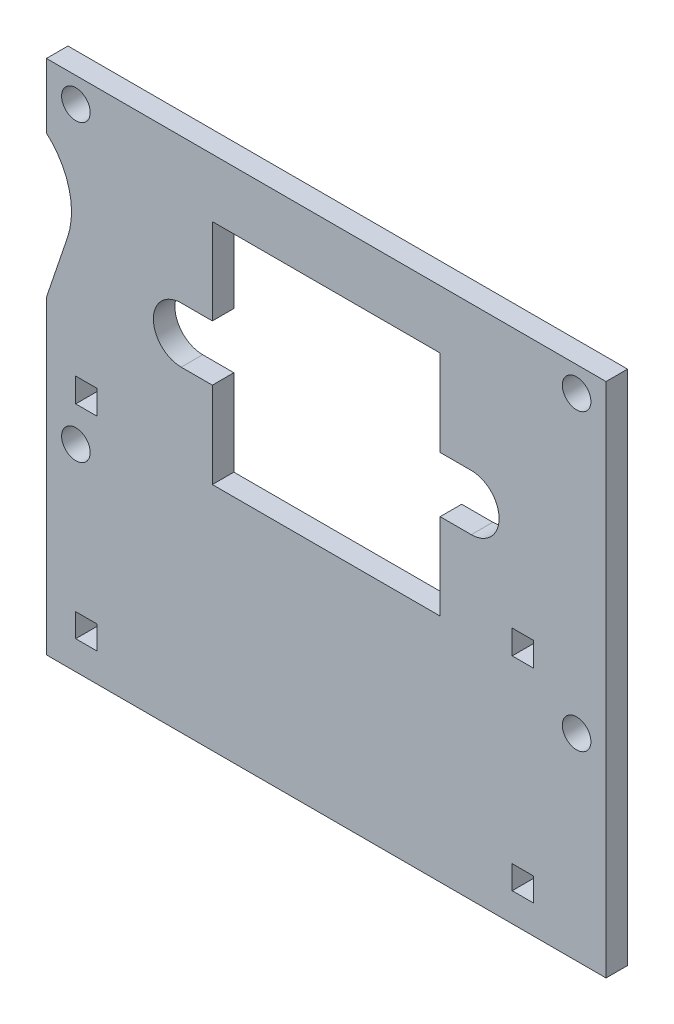
SolidWorks part; units mm, degrees
material "Beech"
ref_plane "Front Plane" through (0, 0, 0) normal (0, 0, 1) x (1, 0, 0)
ref_plane "Top Plane" through (0, 0, 0) normal (0, 1, 0) x (1, 0, 0)
ref_plane "Right Plane" through (0, 0, 0) normal (1, 0, 0) x (0, 0, -1)
sketch "Sketch1" plane through (0, 0, 0) normal (0, 0, 1) x (1, 0, 0)
  line L0 (-20.6375, 0) -> (20.6375, 0)
  line L1 (-20.6375, 22.8481) -> (-19.0799, 27.45)
  line L2 (13.716, 3.8411) -> (13.716, 2.1139)
  line L3 (-18.4785, 3.8411) -> (-16.891, 3.8411)
  line L4 (-18.4785, 3.8411) -> (-18.4785, 2.1139)
  line L5 (-18.4785, 2.1139) -> (-16.891, 2.1139)
  line L6 (-16.891, 3.8411) -> (-16.891, 2.1139)
  line L7 (15.3035, 2.1139) -> (13.716, 2.1139)
  line L8 (15.3035, 3.8411) -> (15.3035, 2.1139)
  line L9 (15.3035, 3.8411) -> (13.716, 3.8411)
  line L22 (-16.891, 17.1139) -> (-16.891, 18.8919)
  line L23 (-18.4785, 17.1139) -> (-16.891, 17.1139)
  line L24 (-18.4785, 18.8919) -> (-18.4785, 17.1139)
  line L25 (-16.891, 18.8919) -> (-18.4785, 18.8919)
  line L26 (-16.891, 17.1139) -> (-16.891, 18.8919)
  line L27 (-18.4785, 17.1139) -> (-16.891, 17.1139)
  line L28 (-18.4785, 18.8919) -> (-18.4785, 17.1139)
  line L29 (-16.891, 18.8919) -> (-18.4785, 18.8919)
  line L44 (0, 14.605) -> (0, 24.13) construction
  line L45 (-8.4, 23.35) -> (-8.4, 17)
  line L46 (-20.6375, 0) -> (-20.6375, 38.1)
  line L47 (-20.6375, 38.1) -> (20.6375, 38.1)
  line L48 (20.6375, 0) -> (20.6375, 38.1)
  line L49 (-20.6375, 25.4) -> (20.6375, 25.4) construction
  line L50 (8.4, 33.8) -> (-8.4, 33.8)
  line L53 (-18.4785, 2.1139) -> (-18.4785, 3.8919) construction
  line L58 (15.3035, 17.1139) -> (15.3035, 18.8919)
  line L59 (13.716, 17.1139) -> (15.3035, 17.1139)
  line L60 (8.4, 33.8) -> (8.4, 27.45)
  line L61 (8.4, 17) -> (-8.4, 17)
  line L62 (-8.4, 33.8) -> (-8.4, 27.45)
  line L63 (8.4, 33.8) -> (-8.4, 17) construction
  line L64 (8.4, 17) -> (-8.4, 33.8) construction
  line L65 (13.716, 18.8919) -> (13.716, 17.1139)
  line L66 (-8.4, 23.35) -> (-10.7, 23.35)
  line L67 (8.4, 23.35) -> (10.7, 23.35)
  line L68 (-8.4, 27.45) -> (-10.7, 27.45)
  line L69 (8.4, 27.45) -> (10.7, 27.45)
  line L70 (15.3035, 18.8919) -> (13.716, 18.8919)
  line L71 (8.4, 23.35) -> (8.4, 17)
  line L72 (15.3035, 17.1139) -> (15.3035, 18.8919)
  line L73 (13.716, 17.1139) -> (15.3035, 17.1139)
  line L74 (13.716, 18.8919) -> (13.716, 17.1139)
  line L75 (15.3035, 18.8919) -> (13.716, 18.8919)
  arc A0 (-10.7, 23.35) -> (-10.7, 27.45) centre (-10.7, 25.4) cw
  arc A1 (10.7, 23.35) -> (10.7, 27.45) centre (10.7, 25.4) ccw
  circle A2 centre (-18.4658, 36.2585) radius 1.0541
  circle A3 centre (-18.4658, 14.5415) radius 1.0541
  circle A4 centre (18.4658, 14.5415) radius 1.0541
  circle A5 centre (18.4658, 36.2585) radius 1.0541
  arc A6 (-20.6375, 33.337) -> (-19.0799, 27.45) centre (-24.3025, 29.2177) cw
  point P0 (0, 0)
  point P56 (0, 25.4)
  point P60 (0, 38.1)
  dimension "D14" = 12.7
  dimension "D4" = 2.1082
  dimension "D3" = 38.1
  dimension "D9" = 0
  dimension "D11" = 0
  dimension "D12" = 41.275
  dimension "D13" = 13.716
  dimension "D15" = 16.8
  dimension "D16" = 2.1139
  dimension "D17" = 2.1139
  dimension "D19" = 16.8
  dimension "D20" = 4.1
  dimension "D21" = 2.3
  dimension "D5" = 2.1717
  dimension "D6" = 1.8415
  dimension "D7" = 1.7272
  dimension "D8" = 1.5875
extrude "Boss-Extrude1" add sketch "Sketch1" along normal blind 1.5875
fillet "Fillet7" [suppressed] radius 15.24
